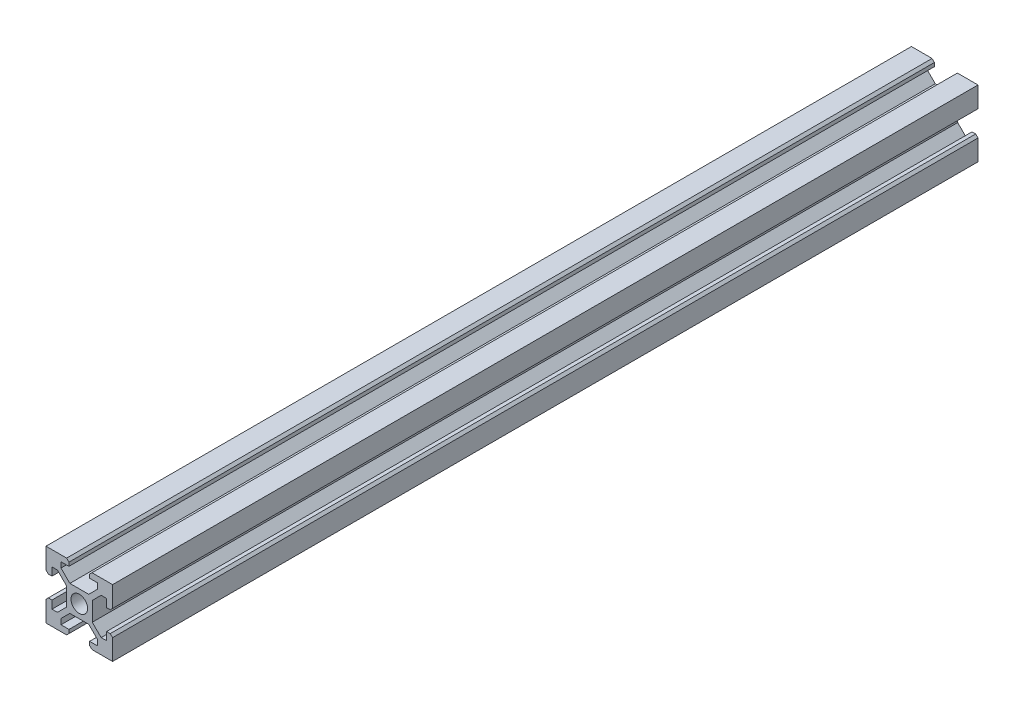
SolidWorks part; units mm, degrees
material "Cast Alloy Steel"
ref_plane "Front Plane" through (0, 0, 0) normal (0, 0, 1) x (1, 0, 0)
ref_plane "Top Plane" through (0, 0, 0) normal (0, 1, 0) x (1, 0, 0)
ref_plane "Right Plane" through (0, 0, 0) normal (1, 0, 0) x (0, 0, -1)
sketch "Sketch1" plane through (0, 0, 0) normal (0, 0, 1) x (1, 0, 0)
  line L0 (3.9, -2.8393) -> (6.5607, -5.5)
  line L1 (-10, 10) -> (10, 10) construction
  line L2 (-10, 10) -> (-10, -10) construction
  line L3 (-10, -10) -> (10, -10) construction
  line L4 (10, 10) -> (10, -10) construction
  line L5 (-10, 10) -> (10, -10) construction
  line L6 (-10, -10) -> (10, 10) construction
  line L7 (-3.9, -3.9) -> (3.9, -3.9) construction
  line L8 (-3.9, -3.9) -> (-3.9, 3.9) construction
  line L9 (-3.9, 3.9) -> (3.9, 3.9) construction
  line L10 (3.9, -3.9) -> (3.9, 3.9) construction
  line L11 (-3.9, -3.9) -> (3.9, 3.9) construction
  line L12 (-3.9, 3.9) -> (3.9, -3.9) construction
  line L13 (-10, 10) -> (-5.5, 10) construction
  line L14 (-10, 10) -> (-10, 5.5) construction
  line L15 (-10, 5.5) -> (-5.5, 5.5) construction
  line L16 (-5.5, 10) -> (-5.5, 5.5) construction
  line L17 (10, 10) -> (5.5, 10) construction
  line L18 (10, 10) -> (10, 5.5) construction
  line L19 (10, 5.5) -> (5.5, 5.5) construction
  line L20 (5.5, 10) -> (5.5, 5.5) construction
  line L21 (-10, -10) -> (-5.5, -10) construction
  line L22 (-10, -10) -> (-10, -5.5) construction
  line L23 (-10, -5.5) -> (-5.5, -5.5) construction
  line L24 (-5.5, -10) -> (-5.5, -5.5) construction
  line L25 (10, -10) -> (5.5, -10) construction
  line L26 (10, -10) -> (10, -5.5) construction
  line L27 (10, -5.5) -> (5.5, -5.5) construction
  line L28 (5.5, -10) -> (5.5, -5.5) construction
  line L29 (2.8393, -3.9) -> (5.5, -6.5607)
  line L30 (-5.5, 6.5607) -> (-2.8393, 3.9)
  line L31 (-6.5607, 5.5) -> (-3.9, 2.8393)
  line L32 (5.5, 6.5607) -> (2.8393, 3.9)
  line L33 (6.5607, 5.5) -> (3.9, 2.8393)
  line L34 (-6.5607, -5.5) -> (-3.9, -2.8393)
  line L35 (-5.5, -6.5607) -> (-2.8393, -3.9)
  line L36 (-2.8393, 3.9) -> (2.8393, 3.9)
  line L37 (-3.9, 2.8393) -> (-3.9, -2.8393)
  line L38 (-2.8393, -3.9) -> (2.8393, -3.9)
  line L39 (3.9, -2.8393) -> (3.9, 2.8393)
  line L40 (5.5, 6.5607) -> (5.5, 8.2007)
  line L41 (5.5, 8.2007) -> (3.1, 8.2007)
  line L42 (3.1, 8.2007) -> (3.1, 9.3)
  line L43 (3.1, 9.3) -> (3.8, 10)
  line L44 (3.8, 10) -> (10, 10)
  line L45 (10, 10) -> (10, 3.8)
  line L46 (10, 3.8) -> (9.3, 3.1)
  line L47 (9.3, 3.1) -> (8.2007, 3.1)
  line L48 (8.2007, 3.1) -> (8.2007, 5.5)
  line L49 (8.2007, 5.5) -> (6.5607, 5.5)
  line L50 (3.1, -8.2007) -> (5.5, -8.2007)
  line L51 (3.1, -9.3) -> (3.1, -8.2007)
  line L52 (3.8, -10) -> (3.1, -9.3)
  line L53 (10, -10) -> (3.8, -10)
  line L54 (10, -3.8) -> (10, -10)
  line L55 (9.3, -3.1) -> (10, -3.8)
  line L56 (8.2007, -3.1) -> (9.3, -3.1)
  line L57 (8.2007, -5.5) -> (8.2007, -3.1)
  line L58 (6.5607, -5.5) -> (8.2007, -5.5)
  line L59 (5.5, -8.2007) -> (5.5, -6.5607)
  line L60 (-8.2007, -3.1) -> (-8.2007, -5.5)
  line L61 (-9.3, -3.1) -> (-8.2007, -3.1)
  line L62 (-10, -3.8) -> (-9.3, -3.1)
  line L63 (-10, -10) -> (-10, -3.8)
  line L64 (-3.8, -10) -> (-10, -10)
  line L65 (-3.1, -9.3) -> (-3.8, -10)
  line L66 (-3.1, -8.2007) -> (-3.1, -9.3)
  line L67 (-5.5, -8.2007) -> (-3.1, -8.2007)
  line L68 (-5.5, -6.5607) -> (-5.5, -8.2007)
  line L69 (-8.2007, -5.5) -> (-6.5607, -5.5)
  line L70 (-3.1, 8.2007) -> (-5.5, 8.2007)
  line L71 (-3.1, 9.3) -> (-3.1, 8.2007)
  line L72 (-3.8, 10) -> (-3.1, 9.3)
  line L73 (-10, 10) -> (-3.8, 10)
  line L74 (-10, 3.8) -> (-10, 10)
  line L75 (-9.3, 3.1) -> (-10, 3.8)
  line L76 (-8.2007, 3.1) -> (-9.3, 3.1)
  line L77 (-8.2007, 5.5) -> (-8.2007, 3.1)
  line L78 (-6.5607, 5.5) -> (-8.2007, 5.5)
  line L79 (-5.5, 8.2007) -> (-5.5, 6.5607)
  circle A0 centre (0, 0) radius 2.5
  point P83 (0, 0)
  dimension "D1" = 5
  dimension "D2" = 20
  dimension "D3" = 7.8
  dimension "D4" = 4.5
  dimension "D5" = 1.5
  dimension "D6" = 0.75
  dimension "D7" = 1.5
  dimension "D8" = 0.75
  dimension "D9" = 1.5
  dimension "D10" = 0.75
  dimension "D11" = 1.5
  dimension "D12" = 0.75
  dimension "D13" = 1.64
  dimension "D14" = 45
  dimension "D15" = 3.1
  dimension "D16" = 6.2
  dimension "D17" = 6.2
  dimension "D18" = 3.1
  dimension "D19" = 4
extrude "Boss-Extrude1" add sketch "Sketch1" along normal mid plane 260 contours L79 L70 L71 L72 L73 L74 L75 L76 L77 L78 L31 L37 L34 L69 L60 L61 L62 L63 L64 L65 L66 L67 L68 L35 L38 L29 L59 L50 L51 L52 L53 L54 L55 L56 L57 L58 L0 L39 L33 L49 L48 L47 L46 L45 L44 L43 L42 L41 L40 L32 L36
